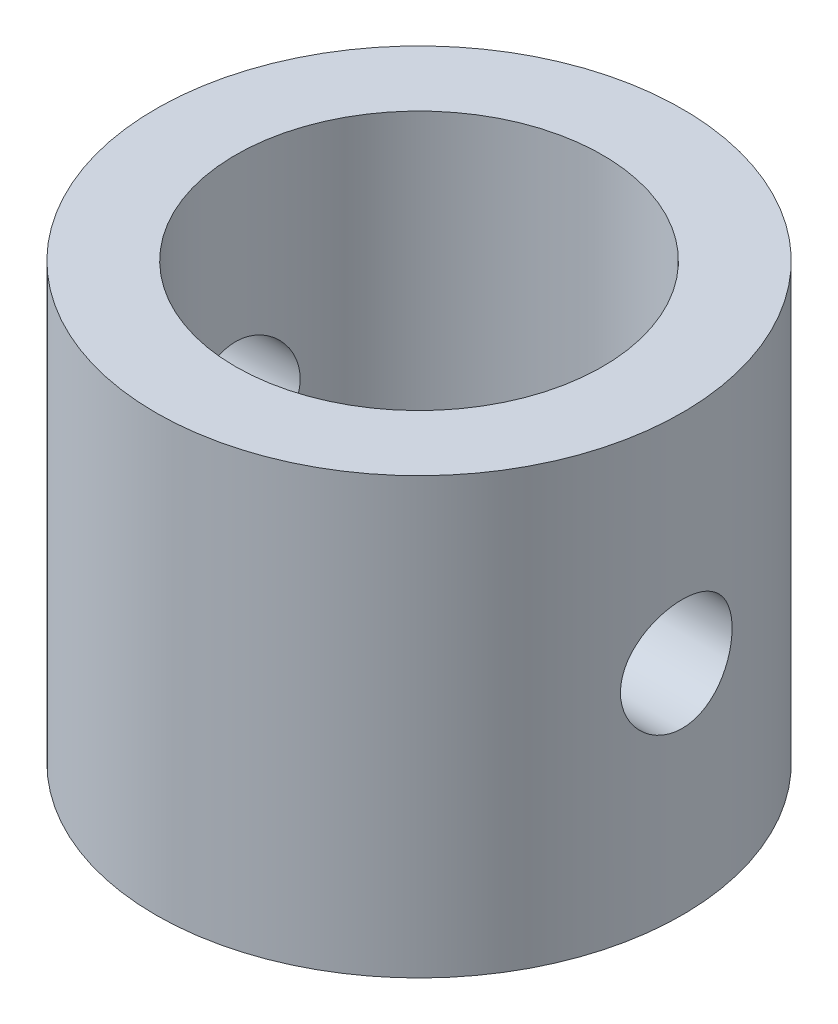
SolidWorks part; units mm, degrees
ref_plane "Front Plane" through (0, 0, 0) normal (1, 0, 0) x (0, 1, 0)
ref_plane "Top Plane" through (0, 0, 0) normal (0, 0, 1) x (0, 1, 0)
ref_plane "Right Plane" through (0, 0, 0) normal (0, 1, 0) x (-1, 0, 0)
sketch "Sketch1" plane through (0, 0, 0) normal (0, 1, 0) x (-1, 0, 0)
  circle A0 centre (0, 0) radius 16.0655
  circle A1 centre (0, 0) radius 23.0505
  dimension "D1" = 46.101
  dimension "D2" = 32.131
extrude "Boss-Extrude1" add sketch "Sketch1" along normal blind 38.1
sketch "Sketch2" plane through (0, 0, 0) normal (1, 0, 0) x (0, 1, 0)
  line L0 (0, 0) -> (19.05, 0) construction
  line L1 (19.05, 0) -> (38.1, 0) construction
  line L2 (38.1, -23.0505) -> (38.1, 23.0505) construction
  circle A0 centre (19.05, 0) radius 4.8895
  dimension "D1" = 9.779
extrude "Cut-Extrude1" cut sketch "Sketch2" against normal through all both and the other way through all
